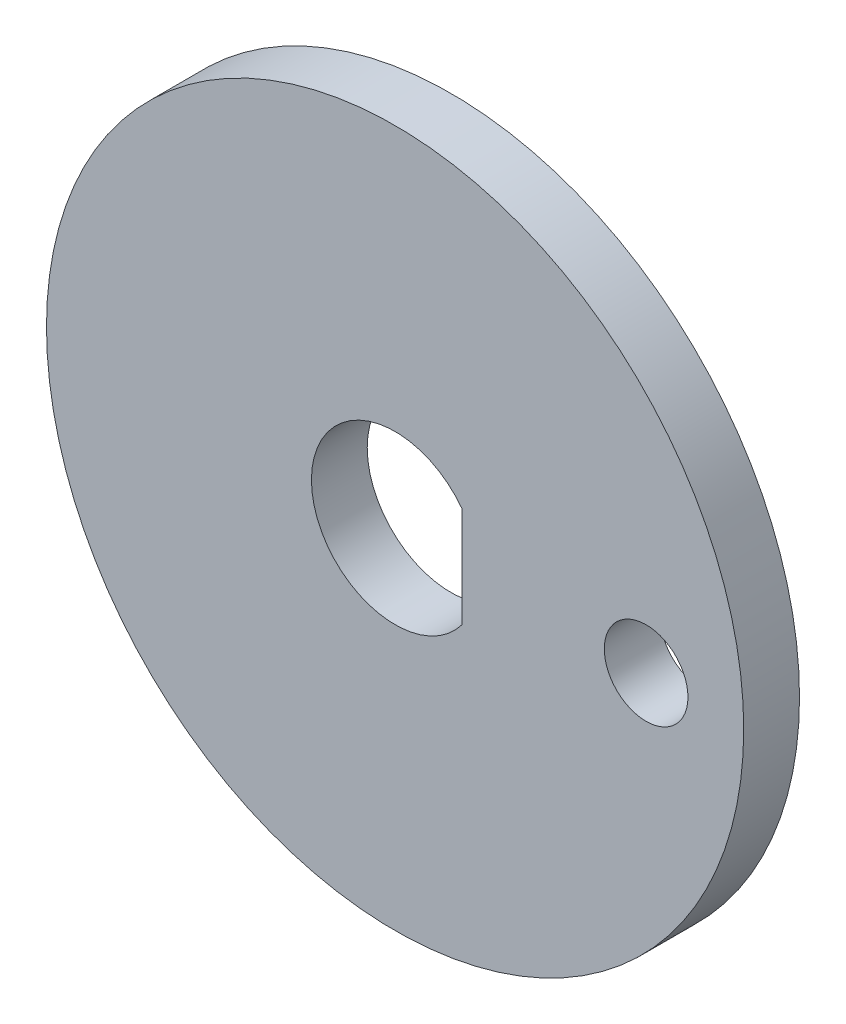
SolidWorks part; units mm, degrees
ref_plane "Front Plane" through (0, 0, 0) normal (0, 0, 1) x (1, 0, 0)
ref_plane "Top Plane" through (0, 0, 0) normal (0, 1, 0) x (1, 0, 0)
ref_plane "Right Plane" through (0, 0, 0) normal (1, 0, 0) x (0, 0, -1)
sketch "Sketch1" plane through (0, 0, 0) normal (0, 0, 1) x (1, 0, 0)
  line L0 (6.9, 0) -> (19.4, 0) construction
  line L1 (9.3, -1.8) -> (9.3, 1.8)
  circle A0 centre (6.9, 0) radius 12.5
  circle A1 centre (15.9, 0) radius 1.5
  arc A3 (9.3, 1.8) -> (9.3, -1.8) centre (6.9, 0) ccw
  dimension "D1" = 25
  dimension "D2" = 3
  dimension "D3" = 9
extrude "Boss-Extrude1" add sketch "Sketch1" along normal blind 2
